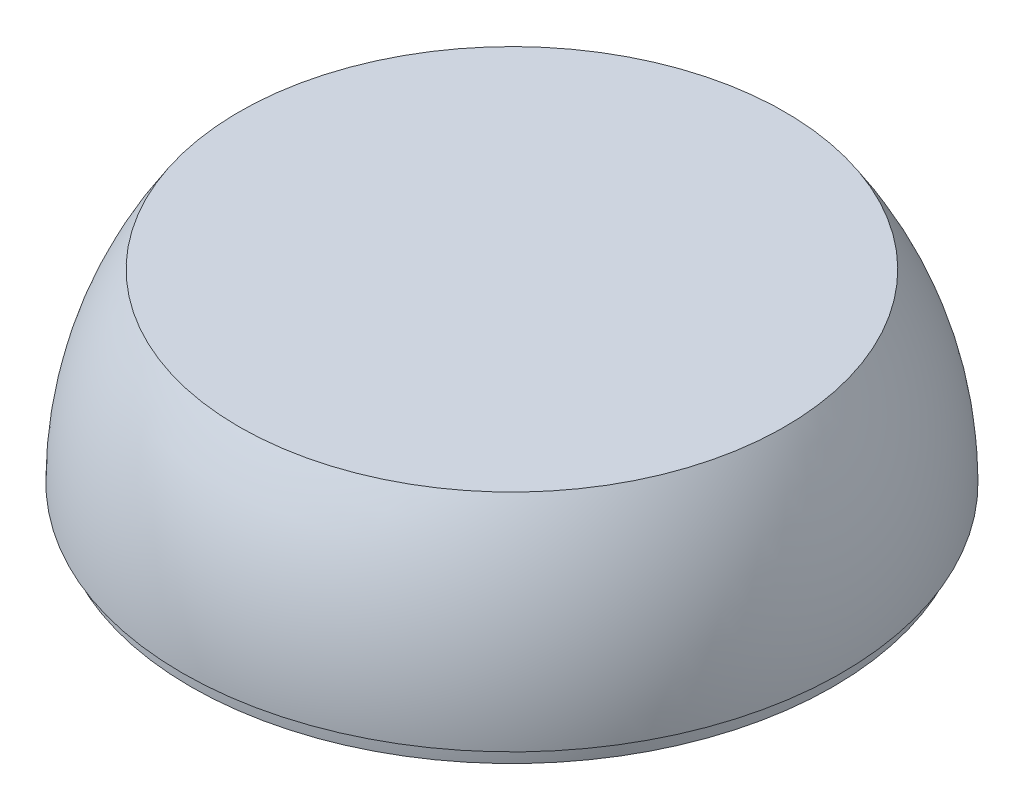
SolidWorks part; units mm, degrees
material "PE Low/Medium Density"
ref_plane "Front Plane" through (0, 0, 0) normal (0, 0, 1) x (1, 0, 0)
ref_plane "Top Plane" through (0, 0, 0) normal (0, 1, 0) x (1, 0, 0)
ref_plane "Right Plane" through (0, 0, 0) normal (1, 0, 0) x (0, 0, -1)
sketch "Sketch1" plane through (0, 0, 0) normal (0, 0, 1) x (1, 0, 0)
  line L13 (0, 0) -> (1, 0)
  line L15 (2.0513, -2) -> (1.05, -2)
  line L24 (41, 23) -> (7.0589, 23)
  line L25 (41, 23) -> (41, 21)
  line L26 (41, 21) -> (8.1366, 21)
  arc A8 (1, 0) -> (1.05, -2) centre (41, 0) ccw
  arc A11 (7.0589, 23) -> (0, 0) centre (41, 0) ccw
  arc A12 (8.1366, 21) -> (2.0513, -2) centre (41, 0) ccw
revolve "Revolve3" add sketch "Sketch1" angle 360 about L25
